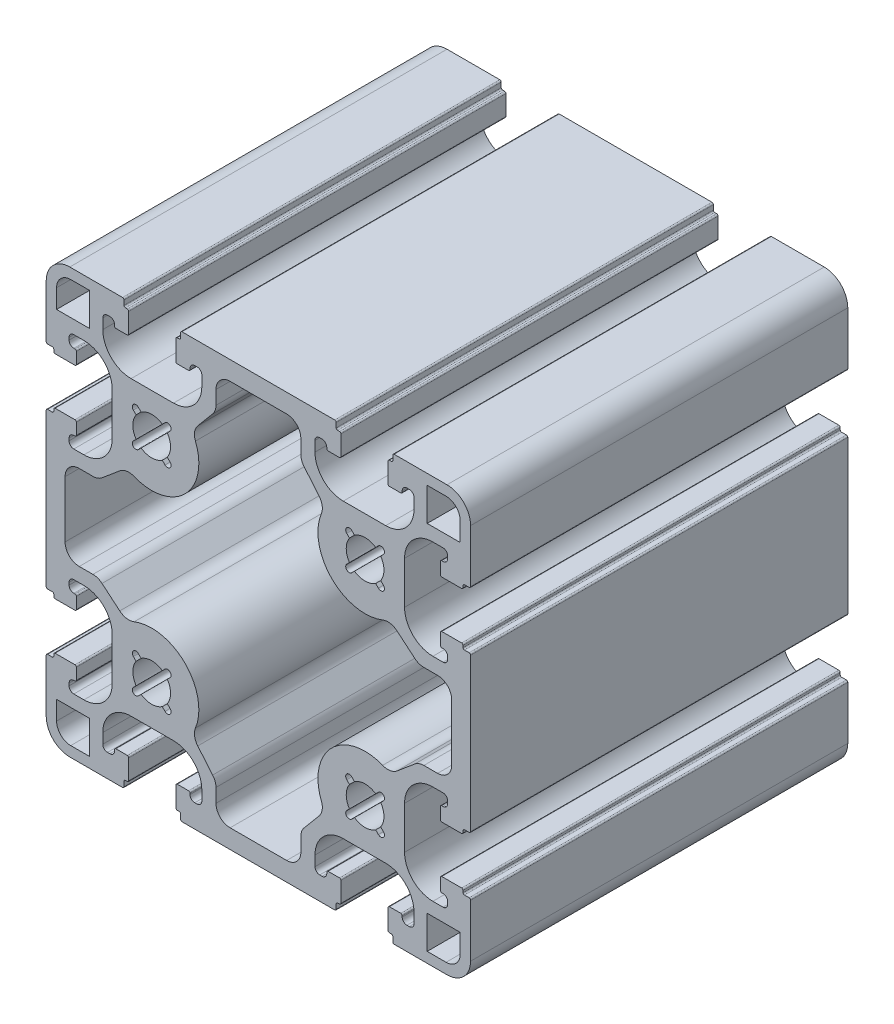
SolidWorks part; units mm, degrees
material "6061 Alaşım"
ref_plane "Ön Düzlem" through (0, 0, 0) normal (0, 0, 1) x (1, 0, 0)
ref_plane "Üst Düzlem" through (0, 0, 0) normal (0, 1, 0) x (1, 0, 0)
ref_plane "Sağ Düzlem" through (0, 0, 0) normal (1, 0, 0) x (0, 0, -1)
sketch "Çizim1" plane through (0, 0, 0) normal (0, 0, 1) x (1, 0, 0)
  line L0 (0, 0) -> (0, 45) construction
  line L5 (-45, -45) -> (45, -45) construction
  line L6 (-45, -45) -> (-45, 45) construction
  line L7 (-45, 45) -> (45, 45) construction
  line L8 (45, -45) -> (45, 45) construction
  line L9 (-45, -45) -> (45, 45) construction
  line L10 (-45, 45) -> (45, -45) construction
  line L11 (0, 45) -> (-16.2, 45)
  line L12 (-16.5, 44.7) -> (-16.5, 43.7)
  line L13 (-16.8, 43.4) -> (-17.2, 43.4)
  line L14 (-17.5, 43.1) -> (-17.5, 38.9)
  line L15 (-17.2, 38.6) -> (-14.8, 38.6)
  line L16 (-14.5, 38.9) -> (-14.5, 39.15)
  line L17 (-13.5, 40.15) -> (-13, 40.15)
  line L18 (-12, 39.15) -> (-12, 37)
  line L19 (-18, 31) -> (-27, 31)
  line L20 (-33, 37) -> (-33, 39.15)
  line L21 (-32, 40.15) -> (-31.5, 40.15)
  line L22 (-30.5, 39.15) -> (-30.5, 38.9)
  line L23 (-30.2, 38.6) -> (-27.8, 38.6)
  line L24 (-27.5, 38.9) -> (-27.5, 43.1)
  line L25 (-27.8, 43.4) -> (-28.2, 43.4)
  line L26 (-28.5, 43.7) -> (-28.5, 44.7)
  line L27 (-28.8, 45) -> (-40, 45)
  line L28 (-35.8, 35.8) -> (-35.8, 42.8)
  line L29 (-35.8, 42.8) -> (-39.8, 42.8)
  line L30 (-12.8612, 29.3984) -> (-9.7019, 33.1635)
  line L31 (-9, 35.0919) -> (-9, 38)
  line L32 (-6, 41) -> (0, 41)
  line L34 (0, 45) -> (0, 41)
  line L35 (-42.8, 35.8) -> (-42.8, 39.8)
  line L36 (-35.8, 35.8) -> (-42.8, 35.8)
  line L37 (-45, 0) -> (-45, 16.2)
  line L38 (-44.7, 16.5) -> (-43.7, 16.5)
  line L39 (-43.4, 16.8) -> (-43.4, 17.2)
  line L40 (-43.1, 17.5) -> (-38.9, 17.5)
  line L41 (-38.6, 17.2) -> (-38.6, 14.8)
  line L42 (-38.9, 14.5) -> (-39.15, 14.5)
  line L43 (-40.15, 13.5) -> (-40.15, 13)
  line L44 (-39.15, 12) -> (-37, 12)
  line L45 (-31, 18) -> (-31, 27)
  line L46 (-37, 33) -> (-39.15, 33)
  line L47 (-40.15, 32) -> (-40.15, 31.5)
  line L48 (-39.15, 30.5) -> (-38.9, 30.5)
  line L49 (-38.6, 30.2) -> (-38.6, 27.8)
  line L50 (-38.9, 27.5) -> (-43.1, 27.5)
  line L51 (-43.4, 27.8) -> (-43.4, 28.2)
  line L52 (-43.7, 28.5) -> (-44.7, 28.5)
  line L53 (-45, 28.8) -> (-45, 40)
  line L54 (-29.3984, 12.8612) -> (-33.1635, 9.7019)
  line L55 (-35.0919, 9) -> (-38, 9)
  line L56 (-41, 6) -> (-41, 0)
  line L57 (-45, 0) -> (-41, 0)
  line L58 (-26.5165, 25.4558) -> (-25.936, 24.8754)
  line L59 (-25.4558, 26.5165) -> (-24.8754, 25.936)
  line L60 (-18.7383, 25.4558) -> (-19.3188, 24.8754)
  line L61 (-19.799, 26.5165) -> (-20.3795, 25.936)
  line L62 (-19.799, 18.7383) -> (-20.3795, 19.3188)
  line L63 (-18.7383, 19.799) -> (-19.3188, 20.3795)
  line L64 (-26.5165, 19.799) -> (-25.936, 20.3795)
  line L65 (-25.4558, 18.7383) -> (-24.8754, 19.3188)
  line L66 (45, 28.8) -> (45, 40)
  line L67 (43.7, 28.5) -> (44.7, 28.5)
  line L68 (43.4, 27.8) -> (43.4, 28.2)
  line L69 (38.9, 27.5) -> (43.1, 27.5)
  line L70 (38.6, 30.2) -> (38.6, 27.8)
  line L71 (39.15, 30.5) -> (38.9, 30.5)
  line L72 (40.15, 32) -> (40.15, 31.5)
  line L73 (37, 33) -> (39.15, 33)
  line L74 (31, 18) -> (31, 27)
  line L75 (39.15, 12) -> (37, 12)
  line L76 (40.15, 13.5) -> (40.15, 13)
  line L77 (38.9, 14.5) -> (39.15, 14.5)
  line L78 (38.6, 17.2) -> (38.6, 14.8)
  line L79 (43.1, 17.5) -> (38.9, 17.5)
  line L80 (43.4, 16.8) -> (43.4, 17.2)
  line L81 (44.7, 16.5) -> (43.7, 16.5)
  line L82 (45, 0) -> (45, 16.2)
  line L83 (45, 0) -> (41, 0)
  line L84 (41, 6) -> (41, 0)
  line L85 (35.0919, 9) -> (38, 9)
  line L86 (29.3984, 12.8612) -> (33.1635, 9.7019)
  line L87 (12.8612, 29.3984) -> (9.7019, 33.1635)
  line L88 (9, 35.0919) -> (9, 38)
  line L89 (6, 41) -> (0, 41)
  line L90 (0, 45) -> (0, 41)
  line L91 (0, 45) -> (16.2, 45)
  line L92 (16.5, 44.7) -> (16.5, 43.7)
  line L93 (16.8, 43.4) -> (17.2, 43.4)
  line L94 (17.5, 43.1) -> (17.5, 38.9)
  line L95 (17.2, 38.6) -> (14.8, 38.6)
  line L96 (14.5, 38.9) -> (14.5, 39.15)
  line L97 (13.5, 40.15) -> (13, 40.15)
  line L98 (12, 39.15) -> (12, 37)
  line L99 (18, 31) -> (27, 31)
  line L100 (33, 37) -> (33, 39.15)
  line L101 (32, 40.15) -> (31.5, 40.15)
  line L102 (30.5, 39.15) -> (30.5, 38.9)
  line L103 (30.2, 38.6) -> (27.8, 38.6)
  line L104 (27.5, 38.9) -> (27.5, 43.1)
  line L105 (27.8, 43.4) -> (28.2, 43.4)
  line L106 (28.5, 43.7) -> (28.5, 44.7)
  line L107 (28.8, 45) -> (40, 45)
  line L108 (25.4558, 26.5165) -> (24.8754, 25.936)
  line L109 (26.5165, 25.4558) -> (25.936, 24.8754)
  line L110 (26.5165, 19.799) -> (25.936, 20.3795)
  line L111 (25.4558, 18.7383) -> (24.8754, 19.3188)
  line L112 (19.799, 18.7383) -> (20.3795, 19.3188)
  line L113 (18.7383, 19.799) -> (19.3188, 20.3795)
  line L114 (18.7383, 25.4558) -> (19.3188, 24.8754)
  line L115 (19.799, 26.5165) -> (20.3795, 25.936)
  line L116 (35.8, 42.8) -> (39.8, 42.8)
  line L117 (42.8, 35.8) -> (42.8, 39.8)
  line L118 (35.8, 35.8) -> (42.8, 35.8)
  line L119 (35.8, 35.8) -> (35.8, 42.8)
  line L120 (0, 0) -> (45, 0) construction
  line L121 (-45, 45) -> (45, -45) construction
  line L122 (28.8, -45) -> (40, -45)
  line L123 (28.5, -43.7) -> (28.5, -44.7)
  line L124 (27.8, -43.4) -> (28.2, -43.4)
  line L125 (27.5, -38.9) -> (27.5, -43.1)
  line L126 (30.2, -38.6) -> (27.8, -38.6)
  line L127 (30.5, -39.15) -> (30.5, -38.9)
  line L128 (32, -40.15) -> (31.5, -40.15)
  line L129 (33, -37) -> (33, -39.15)
  line L130 (18, -31) -> (27, -31)
  line L131 (12, -39.15) -> (12, -37)
  line L132 (13.5, -40.15) -> (13, -40.15)
  line L133 (14.5, -38.9) -> (14.5, -39.15)
  line L134 (17.2, -38.6) -> (14.8, -38.6)
  line L135 (17.5, -43.1) -> (17.5, -38.9)
  line L136 (16.8, -43.4) -> (17.2, -43.4)
  line L137 (16.5, -44.7) -> (16.5, -43.7)
  line L138 (0, -45) -> (16.2, -45)
  line L139 (0, -45) -> (0, -41)
  line L140 (6, -41) -> (0, -41)
  line L141 (9, -35.0919) -> (9, -38)
  line L142 (12.8612, -29.3984) -> (9.7019, -33.1635)
  line L143 (29.3984, -12.8612) -> (33.1635, -9.7019)
  line L144 (35.0919, -9) -> (38, -9)
  line L145 (41, -6) -> (41, 0)
  line L146 (45, 0) -> (41, 0)
  line L147 (45, 0) -> (45, -16.2)
  line L148 (44.7, -16.5) -> (43.7, -16.5)
  line L149 (43.4, -16.8) -> (43.4, -17.2)
  line L150 (43.1, -17.5) -> (38.9, -17.5)
  line L151 (38.6, -17.2) -> (38.6, -14.8)
  line L152 (38.9, -14.5) -> (39.15, -14.5)
  line L153 (40.15, -13.5) -> (40.15, -13)
  line L154 (39.15, -12) -> (37, -12)
  line L155 (31, -18) -> (31, -27)
  line L156 (37, -33) -> (39.15, -33)
  line L157 (40.15, -32) -> (40.15, -31.5)
  line L158 (39.15, -30.5) -> (38.9, -30.5)
  line L159 (38.6, -30.2) -> (38.6, -27.8)
  line L160 (38.9, -27.5) -> (43.1, -27.5)
  line L161 (43.4, -27.8) -> (43.4, -28.2)
  line L162 (43.7, -28.5) -> (44.7, -28.5)
  line L163 (45, -28.8) -> (45, -40)
  line L164 (26.5165, -25.4558) -> (25.936, -24.8754)
  line L165 (25.4558, -26.5165) -> (24.8754, -25.936)
  line L166 (19.799, -26.5165) -> (20.3795, -25.936)
  line L167 (18.7383, -25.4558) -> (19.3188, -24.8754)
  line L168 (18.7383, -19.799) -> (19.3188, -20.3795)
  line L169 (19.799, -18.7383) -> (20.3795, -19.3188)
  line L170 (25.4558, -18.7383) -> (24.8754, -19.3188)
  line L171 (26.5165, -19.799) -> (25.936, -20.3795)
  line L172 (42.8, -35.8) -> (42.8, -39.8)
  line L173 (35.8, -42.8) -> (39.8, -42.8)
  line L174 (35.8, -35.8) -> (35.8, -42.8)
  line L175 (35.8, -35.8) -> (42.8, -35.8)
  line L176 (0, 0) -> (0, -45) construction
  line L177 (45, 45) -> (-45, -45) construction
  line L178 (-45, -28.8) -> (-45, -40)
  line L179 (-43.7, -28.5) -> (-44.7, -28.5)
  line L180 (-43.4, -27.8) -> (-43.4, -28.2)
  line L181 (-38.9, -27.5) -> (-43.1, -27.5)
  line L182 (-38.6, -30.2) -> (-38.6, -27.8)
  line L183 (-39.15, -30.5) -> (-38.9, -30.5)
  line L184 (-40.15, -32) -> (-40.15, -31.5)
  line L185 (-37, -33) -> (-39.15, -33)
  line L186 (-31, -18) -> (-31, -27)
  line L187 (-39.15, -12) -> (-37, -12)
  line L188 (-40.15, -13.5) -> (-40.15, -13)
  line L189 (-38.9, -14.5) -> (-39.15, -14.5)
  line L190 (-38.6, -17.2) -> (-38.6, -14.8)
  line L191 (-43.1, -17.5) -> (-38.9, -17.5)
  line L192 (-43.4, -16.8) -> (-43.4, -17.2)
  line L193 (-44.7, -16.5) -> (-43.7, -16.5)
  line L194 (-45, 0) -> (-45, -16.2)
  line L195 (-45, 0) -> (-41, 0)
  line L196 (-41, -6) -> (-41, 0)
  line L197 (-35.0919, -9) -> (-38, -9)
  line L198 (-29.3984, -12.8612) -> (-33.1635, -9.7019)
  line L199 (-12.8612, -29.3984) -> (-9.7019, -33.1635)
  line L200 (-9, -35.0919) -> (-9, -38)
  line L201 (-6, -41) -> (0, -41)
  line L202 (0, -45) -> (0, -41)
  line L203 (0, -45) -> (-16.2, -45)
  line L204 (-16.5, -44.7) -> (-16.5, -43.7)
  line L205 (-16.8, -43.4) -> (-17.2, -43.4)
  line L206 (-17.5, -43.1) -> (-17.5, -38.9)
  line L207 (-17.2, -38.6) -> (-14.8, -38.6)
  line L208 (-14.5, -38.9) -> (-14.5, -39.15)
  line L209 (-13.5, -40.15) -> (-13, -40.15)
  line L210 (-12, -39.15) -> (-12, -37)
  line L211 (-18, -31) -> (-27, -31)
  line L212 (-33, -37) -> (-33, -39.15)
  line L213 (-32, -40.15) -> (-31.5, -40.15)
  line L214 (-30.5, -39.15) -> (-30.5, -38.9)
  line L215 (-30.2, -38.6) -> (-27.8, -38.6)
  line L216 (-27.5, -38.9) -> (-27.5, -43.1)
  line L217 (-27.8, -43.4) -> (-28.2, -43.4)
  line L218 (-28.5, -43.7) -> (-28.5, -44.7)
  line L219 (-28.8, -45) -> (-40, -45)
  line L220 (-25.4558, -26.5165) -> (-24.8754, -25.936)
  line L221 (-26.5165, -25.4558) -> (-25.936, -24.8754)
  line L222 (-26.5165, -19.799) -> (-25.936, -20.3795)
  line L223 (-25.4558, -18.7383) -> (-24.8754, -19.3188)
  line L224 (-19.799, -18.7383) -> (-20.3795, -19.3188)
  line L225 (-18.7383, -19.799) -> (-19.3188, -20.3795)
  line L226 (-18.7383, -25.4558) -> (-19.3188, -24.8754)
  line L227 (-19.799, -26.5165) -> (-20.3795, -25.936)
  line L228 (-35.8, -42.8) -> (-39.8, -42.8)
  line L229 (-42.8, -35.8) -> (-42.8, -39.8)
  line L230 (-35.8, -35.8) -> (-42.8, -35.8)
  line L231 (-35.8, -35.8) -> (-35.8, -42.8)
  line L232 (0, 0) -> (-45, 0) construction
  line L233 (45, -45) -> (-45, 45) construction
  circle A0 centre (-22.6274, 22.6274) radius 4 construction
  circle A1 centre (-22.6274, 22.6274) radius 10 construction
  arc A2 (-12, 37) -> (-18, 31) centre (-18, 37) cw
  arc A3 (-27, 31) -> (-33, 37) centre (-27, 37) cw
  arc A4 (-16.2, 45) -> (-16.5, 44.7) centre (-16.2, 44.7) ccw
  arc A5 (-16.5, 43.7) -> (-16.8, 43.4) centre (-16.8, 43.7) cw
  arc A6 (-17.2, 43.4) -> (-17.5, 43.1) centre (-17.2, 43.1) ccw
  arc A7 (-14.8, 38.6) -> (-14.5, 38.9) centre (-14.8, 38.9) ccw
  arc A8 (-17.5, 38.9) -> (-17.2, 38.6) centre (-17.2, 38.9) ccw
  arc A9 (-30.5, 38.9) -> (-30.2, 38.6) centre (-30.2, 38.9) ccw
  arc A10 (-27.8, 38.6) -> (-27.5, 38.9) centre (-27.8, 38.9) ccw
  arc A11 (-27.5, 43.1) -> (-27.8, 43.4) centre (-27.8, 43.1) ccw
  arc A12 (-28.5, 44.7) -> (-28.8, 45) centre (-28.8, 44.7) ccw
  arc A13 (-28.2, 43.4) -> (-28.5, 43.7) centre (-28.2, 43.7) cw
  arc A14 (-13, 40.15) -> (-12, 39.15) centre (-13, 39.15) cw
  arc A15 (-14.5, 39.15) -> (-13.5, 40.15) centre (-13.5, 39.15) cw
  arc A16 (-31.5, 40.15) -> (-30.5, 39.15) centre (-31.5, 39.15) cw
  arc A17 (-33, 39.15) -> (-32, 40.15) centre (-32, 39.15) cw
  arc A18 (-26.3525, 13.3471) -> (-13.3471, 26.3525) centre (-22.6274, 22.6274) ccw
  arc A19 (-13.3471, 26.3525) -> (-12.8612, 29.3984) centre (-10.5631, 27.4701) cw
  arc A20 (-9, 38) -> (-6, 41) centre (-6, 38) cw
  arc A21 (-9.7019, 33.1635) -> (-9, 35.0919) centre (-12, 35.0919) ccw
  arc A22 (-45, 16.2) -> (-44.7, 16.5) centre (-44.7, 16.2) cw
  arc A23 (-43.7, 16.5) -> (-43.4, 16.8) centre (-43.7, 16.8) ccw
  arc A24 (-43.4, 17.2) -> (-43.1, 17.5) centre (-43.1, 17.2) cw
  arc A25 (-38.9, 17.5) -> (-38.6, 17.2) centre (-38.9, 17.2) cw
  arc A26 (-38.6, 14.8) -> (-38.9, 14.5) centre (-38.9, 14.8) cw
  arc A27 (-39.15, 14.5) -> (-40.15, 13.5) centre (-39.15, 13.5) ccw
  arc A28 (-40.15, 13) -> (-39.15, 12) centre (-39.15, 13) ccw
  arc A29 (-37, 12) -> (-31, 18) centre (-37, 18) ccw
  arc A30 (-31, 27) -> (-37, 33) centre (-37, 27) ccw
  arc A31 (-39.15, 33) -> (-40.15, 32) centre (-39.15, 32) ccw
  arc A32 (-40.15, 31.5) -> (-39.15, 30.5) centre (-39.15, 31.5) ccw
  arc A33 (-38.9, 30.5) -> (-38.6, 30.2) centre (-38.9, 30.2) cw
  arc A34 (-38.6, 27.8) -> (-38.9, 27.5) centre (-38.9, 27.8) cw
  arc A35 (-43.1, 27.5) -> (-43.4, 27.8) centre (-43.1, 27.8) cw
  arc A36 (-43.4, 28.2) -> (-43.7, 28.5) centre (-43.7, 28.2) ccw
  arc A37 (-44.7, 28.5) -> (-45, 28.8) centre (-44.7, 28.8) cw
  arc A38 (-26.3525, 13.3471) -> (-29.3984, 12.8612) centre (-27.4701, 10.5631) ccw
  arc A39 (-33.1635, 9.7019) -> (-35.0919, 9) centre (-35.0919, 12) cw
  arc A40 (-38, 9) -> (-41, 6) centre (-38, 6) ccw
  arc A41 (-39.8, 42.8) -> (-42.8, 39.8) centre (-39.8, 39.8) ccw
  circle A42 centre (-25.9862, 25.9862) radius 0.75 construction
  arc A43 (-26.5165, 25.4558) -> (-25.4558, 26.5165) centre (-25.9862, 25.9862) cw
  arc A44 (-19.799, 26.5165) -> (-18.7383, 25.4558) centre (-19.2687, 25.9862) cw
  circle A45 centre (-22.6274, 22.6274) radius 4 construction
  arc A46 (-18.7383, 19.799) -> (-19.799, 18.7383) centre (-19.2687, 19.2687) cw
  circle A47 centre (-22.6274, 22.6274) radius 4 construction
  arc A48 (-25.4558, 18.7383) -> (-26.5165, 19.799) centre (-25.9862, 19.2687) cw
  circle A49 centre (-22.6274, 22.6274) radius 4 construction
  arc A50 (-24.8754, 25.936) -> (-20.3795, 25.936) centre (-22.6274, 22.6274) cw
  arc A51 (-19.3188, 24.8754) -> (-19.3188, 20.3795) centre (-22.6274, 22.6274) cw
  arc A52 (-20.3795, 19.3188) -> (-24.8754, 19.3188) centre (-22.6274, 22.6274) cw
  arc A53 (-25.936, 20.3795) -> (-25.936, 24.8754) centre (-22.6274, 22.6274) cw
  arc A54 (-40, 45) -> (-45, 40) centre (-40, 40) ccw
  arc A55 (45, 40) -> (40, 45) centre (40, 40) ccw
  arc A56 (44.7, 28.5) -> (45, 28.8) centre (44.7, 28.8) ccw
  arc A57 (43.4, 28.2) -> (43.7, 28.5) centre (43.7, 28.2) cw
  arc A58 (43.1, 27.5) -> (43.4, 27.8) centre (43.1, 27.8) ccw
  arc A59 (38.6, 27.8) -> (38.9, 27.5) centre (38.9, 27.8) ccw
  arc A60 (38.9, 30.5) -> (38.6, 30.2) centre (38.9, 30.2) ccw
  arc A61 (40.15, 31.5) -> (39.15, 30.5) centre (39.15, 31.5) cw
  arc A62 (39.15, 33) -> (40.15, 32) centre (39.15, 32) cw
  arc A63 (31, 27) -> (37, 33) centre (37, 27) cw
  arc A64 (37, 12) -> (31, 18) centre (37, 18) cw
  arc A65 (40.15, 13) -> (39.15, 12) centre (39.15, 13) cw
  arc A66 (39.15, 14.5) -> (40.15, 13.5) centre (39.15, 13.5) cw
  arc A67 (38.6, 14.8) -> (38.9, 14.5) centre (38.9, 14.8) ccw
  arc A68 (38.9, 17.5) -> (38.6, 17.2) centre (38.9, 17.2) ccw
  arc A69 (43.4, 17.2) -> (43.1, 17.5) centre (43.1, 17.2) ccw
  arc A70 (43.7, 16.5) -> (43.4, 16.8) centre (43.7, 16.8) cw
  arc A71 (45, 16.2) -> (44.7, 16.5) centre (44.7, 16.2) ccw
  arc A72 (38, 9) -> (41, 6) centre (38, 6) cw
  arc A73 (33.1635, 9.7019) -> (35.0919, 9) centre (35.0919, 12) ccw
  arc A74 (26.3525, 13.3471) -> (29.3984, 12.8612) centre (27.4701, 10.5631) cw
  arc A75 (13.3471, 26.3525) -> (26.3525, 13.3471) centre (22.6274, 22.6274) ccw
  arc A76 (13.3471, 26.3525) -> (12.8612, 29.3984) centre (10.5631, 27.4701) ccw
  arc A77 (9.7019, 33.1635) -> (9, 35.0919) centre (12, 35.0919) cw
  arc A78 (9, 38) -> (6, 41) centre (6, 38) ccw
  arc A79 (16.2, 45) -> (16.5, 44.7) centre (16.2, 44.7) cw
  arc A80 (16.5, 43.7) -> (16.8, 43.4) centre (16.8, 43.7) ccw
  arc A81 (17.2, 43.4) -> (17.5, 43.1) centre (17.2, 43.1) cw
  arc A82 (17.5, 38.9) -> (17.2, 38.6) centre (17.2, 38.9) cw
  arc A83 (14.8, 38.6) -> (14.5, 38.9) centre (14.8, 38.9) cw
  arc A84 (14.5, 39.15) -> (13.5, 40.15) centre (13.5, 39.15) ccw
  arc A85 (13, 40.15) -> (12, 39.15) centre (13, 39.15) ccw
  arc A86 (12, 37) -> (18, 31) centre (18, 37) ccw
  arc A87 (27, 31) -> (33, 37) centre (27, 37) ccw
  arc A88 (33, 39.15) -> (32, 40.15) centre (32, 39.15) ccw
  arc A89 (31.5, 40.15) -> (30.5, 39.15) centre (31.5, 39.15) ccw
  arc A90 (30.5, 38.9) -> (30.2, 38.6) centre (30.2, 38.9) cw
  arc A91 (27.8, 38.6) -> (27.5, 38.9) centre (27.8, 38.9) cw
  arc A92 (27.5, 43.1) -> (27.8, 43.4) centre (27.8, 43.1) cw
  arc A93 (28.2, 43.4) -> (28.5, 43.7) centre (28.2, 43.7) ccw
  arc A94 (28.5, 44.7) -> (28.8, 45) centre (28.8, 44.7) cw
  arc A95 (20.3795, 25.936) -> (24.8754, 25.936) centre (22.6274, 22.6274) cw
  arc A96 (25.4558, 26.5165) -> (26.5165, 25.4558) centre (25.9862, 25.9862) cw
  arc A97 (25.936, 24.8754) -> (25.936, 20.3795) centre (22.6274, 22.6274) cw
  arc A98 (26.5165, 19.799) -> (25.4558, 18.7383) centre (25.9862, 19.2687) cw
  arc A99 (24.8754, 19.3188) -> (20.3795, 19.3188) centre (22.6274, 22.6274) cw
  arc A100 (19.799, 18.7383) -> (18.7383, 19.799) centre (19.2687, 19.2687) cw
  arc A101 (19.3188, 20.3795) -> (19.3188, 24.8754) centre (22.6274, 22.6274) cw
  arc A102 (18.7383, 25.4558) -> (19.799, 26.5165) centre (19.2687, 25.9862) cw
  circle A103 centre (22.6274, 22.6274) radius 10 construction
  arc A104 (42.8, 39.8) -> (39.8, 42.8) centre (39.8, 39.8) ccw
  arc A105 (40, -45) -> (45, -40) centre (40, -40) ccw
  arc A106 (28.5, -44.7) -> (28.8, -45) centre (28.8, -44.7) ccw
  arc A107 (28.2, -43.4) -> (28.5, -43.7) centre (28.2, -43.7) cw
  arc A108 (27.5, -43.1) -> (27.8, -43.4) centre (27.8, -43.1) ccw
  arc A109 (27.8, -38.6) -> (27.5, -38.9) centre (27.8, -38.9) ccw
  arc A110 (30.5, -38.9) -> (30.2, -38.6) centre (30.2, -38.9) ccw
  arc A111 (31.5, -40.15) -> (30.5, -39.15) centre (31.5, -39.15) cw
  arc A112 (33, -39.15) -> (32, -40.15) centre (32, -39.15) cw
  arc A113 (27, -31) -> (33, -37) centre (27, -37) cw
  arc A114 (12, -37) -> (18, -31) centre (18, -37) cw
  arc A115 (13, -40.15) -> (12, -39.15) centre (13, -39.15) cw
  arc A116 (14.5, -39.15) -> (13.5, -40.15) centre (13.5, -39.15) cw
  arc A117 (14.8, -38.6) -> (14.5, -38.9) centre (14.8, -38.9) ccw
  arc A118 (17.5, -38.9) -> (17.2, -38.6) centre (17.2, -38.9) ccw
  arc A119 (17.2, -43.4) -> (17.5, -43.1) centre (17.2, -43.1) ccw
  arc A120 (16.5, -43.7) -> (16.8, -43.4) centre (16.8, -43.7) cw
  arc A121 (16.2, -45) -> (16.5, -44.7) centre (16.2, -44.7) ccw
  arc A122 (9, -38) -> (6, -41) centre (6, -38) cw
  arc A123 (9.7019, -33.1635) -> (9, -35.0919) centre (12, -35.0919) ccw
  arc A124 (13.3471, -26.3525) -> (12.8612, -29.3984) centre (10.5631, -27.4701) cw
  arc A125 (26.3525, -13.3471) -> (13.3471, -26.3525) centre (22.6274, -22.6274) ccw
  arc A126 (26.3525, -13.3471) -> (29.3984, -12.8612) centre (27.4701, -10.5631) ccw
  arc A127 (33.1635, -9.7019) -> (35.0919, -9) centre (35.0919, -12) cw
  arc A128 (38, -9) -> (41, -6) centre (38, -6) ccw
  arc A129 (45, -16.2) -> (44.7, -16.5) centre (44.7, -16.2) cw
  arc A130 (43.7, -16.5) -> (43.4, -16.8) centre (43.7, -16.8) ccw
  arc A131 (43.4, -17.2) -> (43.1, -17.5) centre (43.1, -17.2) cw
  arc A132 (38.9, -17.5) -> (38.6, -17.2) centre (38.9, -17.2) cw
  arc A133 (38.6, -14.8) -> (38.9, -14.5) centre (38.9, -14.8) cw
  arc A134 (39.15, -14.5) -> (40.15, -13.5) centre (39.15, -13.5) ccw
  arc A135 (40.15, -13) -> (39.15, -12) centre (39.15, -13) ccw
  arc A136 (37, -12) -> (31, -18) centre (37, -18) ccw
  arc A137 (31, -27) -> (37, -33) centre (37, -27) ccw
  arc A138 (39.15, -33) -> (40.15, -32) centre (39.15, -32) ccw
  arc A139 (40.15, -31.5) -> (39.15, -30.5) centre (39.15, -31.5) ccw
  arc A140 (38.9, -30.5) -> (38.6, -30.2) centre (38.9, -30.2) cw
  arc A141 (38.6, -27.8) -> (38.9, -27.5) centre (38.9, -27.8) cw
  arc A142 (43.1, -27.5) -> (43.4, -27.8) centre (43.1, -27.8) cw
  arc A143 (43.4, -28.2) -> (43.7, -28.5) centre (43.7, -28.2) ccw
  arc A144 (44.7, -28.5) -> (45, -28.8) centre (44.7, -28.8) cw
  arc A145 (25.936, -20.3795) -> (25.936, -24.8754) centre (22.6274, -22.6274) cw
  arc A146 (26.5165, -25.4558) -> (25.4558, -26.5165) centre (25.9862, -25.9862) cw
  arc A147 (24.8754, -25.936) -> (20.3795, -25.936) centre (22.6274, -22.6274) cw
  arc A148 (19.799, -26.5165) -> (18.7383, -25.4558) centre (19.2687, -25.9862) cw
  arc A149 (19.3188, -24.8754) -> (19.3188, -20.3795) centre (22.6274, -22.6274) cw
  arc A150 (18.7383, -19.799) -> (19.799, -18.7383) centre (19.2687, -19.2687) cw
  arc A151 (20.3795, -19.3188) -> (24.8754, -19.3188) centre (22.6274, -22.6274) cw
  arc A152 (25.4558, -18.7383) -> (26.5165, -19.799) centre (25.9862, -19.2687) cw
  circle A153 centre (22.6274, -22.6274) radius 10 construction
  arc A154 (39.8, -42.8) -> (42.8, -39.8) centre (39.8, -39.8) ccw
  arc A155 (-45, -40) -> (-40, -45) centre (-40, -40) ccw
  arc A156 (-44.7, -28.5) -> (-45, -28.8) centre (-44.7, -28.8) ccw
  arc A157 (-43.4, -28.2) -> (-43.7, -28.5) centre (-43.7, -28.2) cw
  arc A158 (-43.1, -27.5) -> (-43.4, -27.8) centre (-43.1, -27.8) ccw
  arc A159 (-38.6, -27.8) -> (-38.9, -27.5) centre (-38.9, -27.8) ccw
  arc A160 (-38.9, -30.5) -> (-38.6, -30.2) centre (-38.9, -30.2) ccw
  arc A161 (-40.15, -31.5) -> (-39.15, -30.5) centre (-39.15, -31.5) cw
  arc A162 (-39.15, -33) -> (-40.15, -32) centre (-39.15, -32) cw
  arc A163 (-31, -27) -> (-37, -33) centre (-37, -27) cw
  arc A164 (-37, -12) -> (-31, -18) centre (-37, -18) cw
  arc A165 (-40.15, -13) -> (-39.15, -12) centre (-39.15, -13) cw
  arc A166 (-39.15, -14.5) -> (-40.15, -13.5) centre (-39.15, -13.5) cw
  arc A167 (-38.6, -14.8) -> (-38.9, -14.5) centre (-38.9, -14.8) ccw
  arc A168 (-38.9, -17.5) -> (-38.6, -17.2) centre (-38.9, -17.2) ccw
  arc A169 (-43.4, -17.2) -> (-43.1, -17.5) centre (-43.1, -17.2) ccw
  arc A170 (-43.7, -16.5) -> (-43.4, -16.8) centre (-43.7, -16.8) cw
  arc A171 (-45, -16.2) -> (-44.7, -16.5) centre (-44.7, -16.2) ccw
  arc A172 (-38, -9) -> (-41, -6) centre (-38, -6) cw
  arc A173 (-33.1635, -9.7019) -> (-35.0919, -9) centre (-35.0919, -12) ccw
  arc A174 (-26.3525, -13.3471) -> (-29.3984, -12.8612) centre (-27.4701, -10.5631) cw
  arc A175 (-13.3471, -26.3525) -> (-26.3525, -13.3471) centre (-22.6274, -22.6274) ccw
  arc A176 (-13.3471, -26.3525) -> (-12.8612, -29.3984) centre (-10.5631, -27.4701) ccw
  arc A177 (-9.7019, -33.1635) -> (-9, -35.0919) centre (-12, -35.0919) cw
  arc A178 (-9, -38) -> (-6, -41) centre (-6, -38) ccw
  arc A179 (-16.2, -45) -> (-16.5, -44.7) centre (-16.2, -44.7) cw
  arc A180 (-16.5, -43.7) -> (-16.8, -43.4) centre (-16.8, -43.7) ccw
  arc A181 (-17.2, -43.4) -> (-17.5, -43.1) centre (-17.2, -43.1) cw
  arc A182 (-17.5, -38.9) -> (-17.2, -38.6) centre (-17.2, -38.9) cw
  arc A183 (-14.8, -38.6) -> (-14.5, -38.9) centre (-14.8, -38.9) cw
  arc A184 (-14.5, -39.15) -> (-13.5, -40.15) centre (-13.5, -39.15) ccw
  arc A185 (-13, -40.15) -> (-12, -39.15) centre (-13, -39.15) ccw
  arc A186 (-12, -37) -> (-18, -31) centre (-18, -37) ccw
  arc A187 (-27, -31) -> (-33, -37) centre (-27, -37) ccw
  arc A188 (-33, -39.15) -> (-32, -40.15) centre (-32, -39.15) ccw
  arc A189 (-31.5, -40.15) -> (-30.5, -39.15) centre (-31.5, -39.15) ccw
  arc A190 (-30.5, -38.9) -> (-30.2, -38.6) centre (-30.2, -38.9) cw
  arc A191 (-27.8, -38.6) -> (-27.5, -38.9) centre (-27.8, -38.9) cw
  arc A192 (-27.5, -43.1) -> (-27.8, -43.4) centre (-27.8, -43.1) cw
  arc A193 (-28.2, -43.4) -> (-28.5, -43.7) centre (-28.2, -43.7) ccw
  arc A194 (-28.5, -44.7) -> (-28.8, -45) centre (-28.8, -44.7) cw
  arc A195 (-20.3795, -25.936) -> (-24.8754, -25.936) centre (-22.6274, -22.6274) cw
  arc A196 (-25.4558, -26.5165) -> (-26.5165, -25.4558) centre (-25.9862, -25.9862) cw
  arc A197 (-25.936, -24.8754) -> (-25.936, -20.3795) centre (-22.6274, -22.6274) cw
  arc A198 (-26.5165, -19.799) -> (-25.4558, -18.7383) centre (-25.9862, -19.2687) cw
  arc A199 (-24.8754, -19.3188) -> (-20.3795, -19.3188) centre (-22.6274, -22.6274) cw
  arc A200 (-19.799, -18.7383) -> (-18.7383, -19.799) centre (-19.2687, -19.2687) cw
  arc A201 (-19.3188, -20.3795) -> (-19.3188, -24.8754) centre (-22.6274, -22.6274) cw
  arc A202 (-18.7383, -25.4558) -> (-19.799, -26.5165) centre (-19.2687, -25.9862) cw
  circle A203 centre (-22.6274, -22.6274) radius 10 construction
  arc A204 (-42.8, -39.8) -> (-39.8, -42.8) centre (-39.8, -39.8) ccw
  point P0 (0, 0)
  point P34 (-16.5, 45)
  point P37 (-16.5, 43.4)
  point P40 (-17.5, 43.4)
  point P45 (-17.5, 38.6)
  point P48 (-30.5, 38.6)
  point P51 (-27.5, 38.6)
  point P56 (-28.5, 45)
  point P78 (-14.1253, 27.8919)
  point P83 (-9, 34)
  point P145 (-42.8, 42.8)
  point P173 (-22.6274, 22.6274)
  point P649 (0, 0)
  dimension "D3" = 8
  dimension "D5" = 20
  dimension "D17" = 6
  dimension "D18" = 0.3
  dimension "D19" = 1
  dimension "D25" = 3
  dimension "D27" = 3
  dimension "D28" = 3
  dimension "D29" = 1.5
  dimension "D31" = 5
  dimension "D1" = 90
  dimension "D2" = 90
  dimension "D4" = 32
  dimension "D6" = 4.85
  dimension "D7" = 1
  dimension "D8" = 1.6
  dimension "D9" = 4.8
  dimension "D10" = 3
  dimension "D11" = 2.5
  dimension "D12" = 12
  dimension "D13" = 14
  dimension "D14" = 10
  dimension "D15" = 3
  dimension "D16" = 21
  dimension "D20" = 2.2
  dimension "D21" = 2.8
  dimension "D22" = 4
  dimension "D23" = 9
  dimension "D24" = 40
  dimension "D26" = 7
  dimension "D30" = 4
  dimension "D32" = 4
extrude "Yükseklik-Ekstrüzyon1" add sketch "Çizim1" against normal blind 80 contours A194 L218 A193 L217 A192 L216 A191 L215 A190 L214 A189 L213 A188 L212 A187 L211 A186 L210 A185 L209 A184 L208 A183 L207 A182 L206 A181 L205 A180 L204 A179 L203 L139 L201 A178 L200 A177 L199 A176 A175 A174 L198 A173 L197 A172 L196 L57 L194 A171 L193 A170 | A144 L162 A143 L161 A142 L160 A141 L159 A140 L158 A139 L157 A138 L156 A137 L155 A136 L154 A135 L153 A134 L152 A133 L151 A132 L150 A131 L149 A130 L148 A129 L147 L83 L145 A128 L144 A127 L143 A126 A125 A124 L142 A123 L141 A122 L140 L139 L138 A121 L137 A120 | A94 L106 A93 L105 A92 L104 A91 L103 A90 L102 A89 L101 A88 L100 A87 L99 A86 L98 A85 L97 A84 L96 A83 L95 A82 L94 A81 L93 A80 L92 A79 L91 L34 L89 A78 L88 A77 L87 A76 A75 A74 L86 A73 L85 A72 L84 L83 L82 A71 L81 A70 | L27 A54 L53 A37 L52 A36 L51 A35 L50 A34 L49 A33 L48 A32 L47 A31 L46 A30 L45 A29 L44 A28 L43 A27 L42 A26 L41 A25 L40 A24 L39 A23 L38 A22 L37 L57 L56 A40 L55 A39 L54 A38 A18 A19 L30 A21 L31 A20 L32 L34 L11
